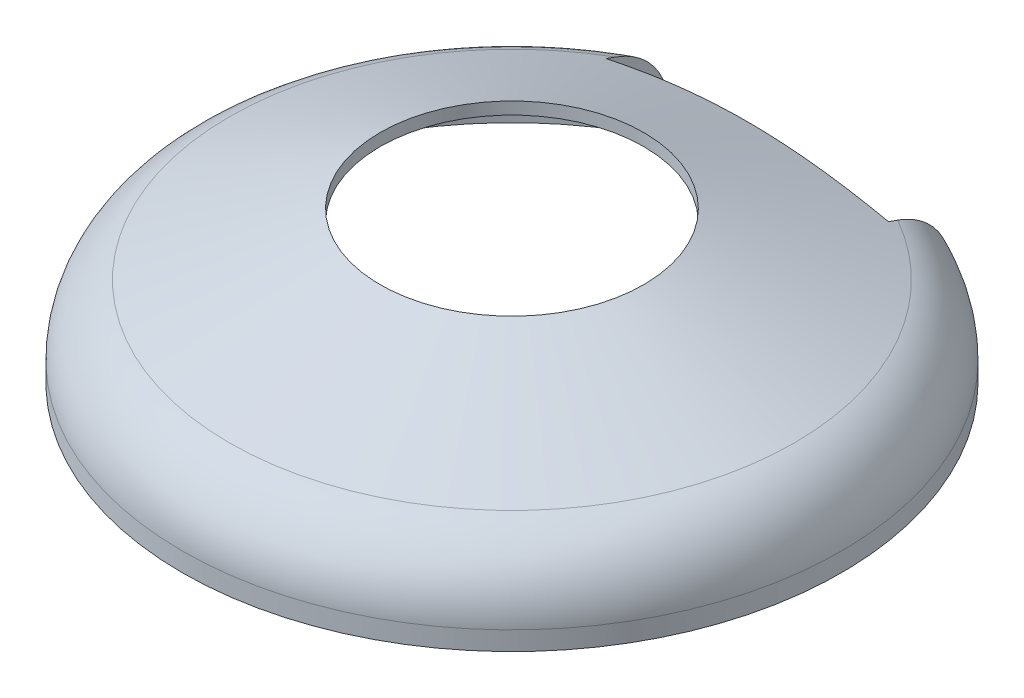
SolidWorks part; units mm, degrees
ref_plane "Front Plane" through (0, 0, 0) normal (0, 0, 1) x (1, 0, 0)
ref_plane "Top Plane" through (0, 0, 0) normal (0, 1, 0) x (1, 0, 0)
ref_plane "Right Plane" through (0, 0, 0) normal (1, 0, 0) x (0, 0, -1)
sketch "Sketch1" plane through (0, 0, 0) normal (0, 0, 1) x (1, 0, 0)
  line L0 (0, 40) -> (0, 0)
  line L1 (0, 0) -> (-87.5, 0)
  line L4 (-35, 40) -> (0, 40)
  line L5 (-87.5, 0) -> (-87.5, 5)
  line L6 (-75, 23.6243) -> (-35, 40)
  arc A1 (-87.5, 5) -> (-75, 23.6243) centre (-67.3754, 5) cw
  dimension "D1" = 87.5
  dimension "D2" = 40
  dimension "D3" = 5
  dimension "D4" = 35
  dimension "D5" = 40
revolve "Revolve1" add sketch "Sketch1" angle 360 about L0
shell "Shell1" thickness 3
sketch "Sketch2" plane through (0, 40, 0) normal (0, 1, 0) x (1, 0, 0)
  circle A0 centre (0, 0) radius 35 construction
  circle A1 centre (0, 0) radius 35
extrude "Cut-Extrude1" cut sketch "Sketch2" against normal through all
sketch "Sketch3" plane through (0, 0, 0) normal (0, 1, 0) x (1, 0, 0)
  line L1 (-37.5, 112.5) -> (37.5, 112.5)
  line L2 (-37.5, 112.5) -> (-37.5, 62.5)
  line L3 (-37.5, 62.5) -> (37.5, 62.5)
  line L4 (37.5, 112.5) -> (37.5, 62.5)
  line L5 (-37.5, 112.5) -> (37.5, 62.5) construction
  line L6 (-37.5, 62.5) -> (37.5, 112.5) construction
  circle A0 centre (0, 0) radius 87.5 construction
  point P0 (0, 87.5)
  dimension "D1" = 75
  dimension "D2" = 50
extrude "Cut-Extrude2" cut sketch "Sketch3" along normal through all
